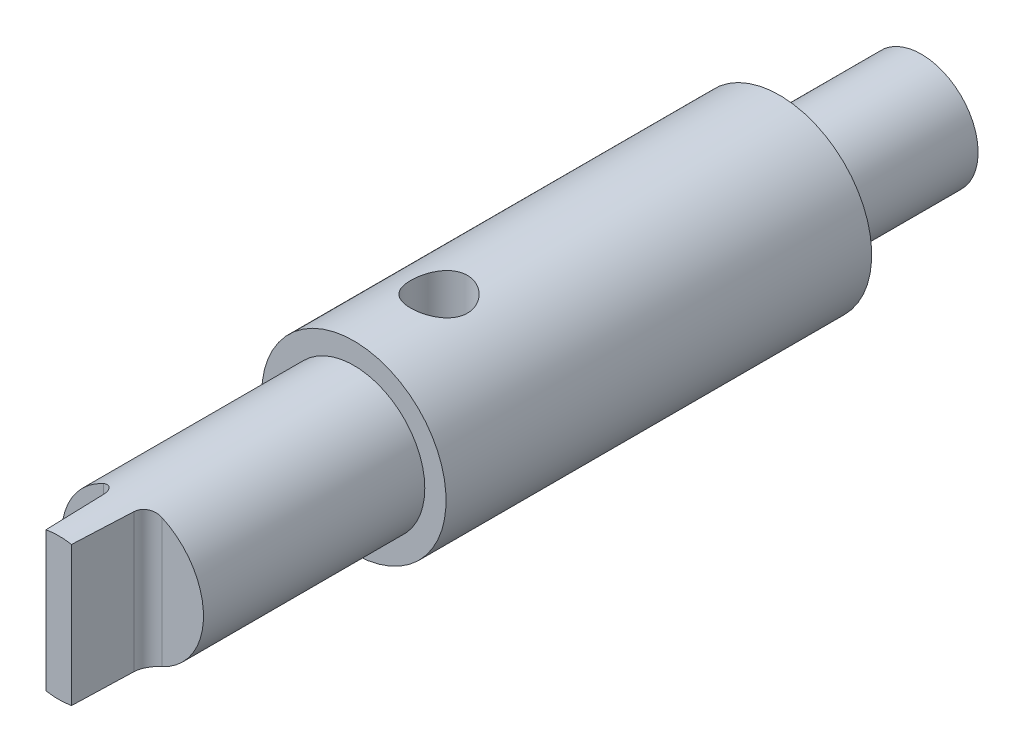
SolidWorks part; units mm, degrees
ref_plane "Спереди" through (0, 0, 0) normal (0, 0, 1) x (1, 0, 0)
ref_plane "Сверху" through (0, 0, 0) normal (0, 1, 0) x (1, 0, 0)
ref_plane "Справа" through (0, 0, 0) normal (1, 0, 0) x (0, 0, -1)
sketch "Эскиз1" plane through (0, 0, 0) normal (0, 0, 1) x (1, 0, 0)
  circle A0 centre (0, 0) radius 2.5
  dimension "D1" = 5
extrude "Бобышка-Вытянуть1" add sketch "Эскиз1" along normal blind 10.4
sketch "Эскиз2" plane through (0, 0, 0) normal (0, 0, -1) x (-1, 0, 0)
  circle A0 centre (0, 0) radius 3.25
  dimension "D1" = 6.5
extrude "Бобышка-Вытянуть2" add sketch "Эскиз2" along normal blind 15
sketch "Эскиз4" plane through (0, 0, 0) normal (0, 1, 0) x (1, 0, 0)
  line L0 (0, -10.4) -> (0, 0) construction
  line L1 (-2.5, -10.4) -> (2.5, -10.4) construction
  line L2 (-0.45, -10.4) -> (-0.55, -7.8)
  line L3 (-0.55, -7.8) -> (-2.5, -7.8)
  line L4 (-2.5, 0) -> (-2.5, -10.4) construction
  line L5 (-2.5, -7.8) -> (-2.5, -10.4)
  line L6 (-2.5, -10.4) -> (-0.45, -10.4)
  line L7 (0.45, -10.4) -> (0.55, -7.8)
  line L8 (0.55, -7.8) -> (2.5, -7.8)
  line L9 (2.5, -7.8) -> (2.5, -10.4)
  line L10 (2.5, -10.4) -> (0.45, -10.4)
  dimension "D1" = 0.45
  dimension "D2" = 0.55
  dimension "D3" = 2.6
extrude "Вырез-Вытянуть1" cut sketch "Эскиз4" against normal through all both and the other way through all
fillet "Скругление1" radius 0.5 2 edges at (0.55, 0, 7.8) (-0.55, 0, 7.8)
sketch "Эскиз5" plane through (0, 0, 0) normal (0, 1, 0) x (1, 0, 0)
  line L0 (-2.5, 0) -> (2.5, 0) construction
  circle A0 centre (0, 3) radius 1
  dimension "D2" = 2
  dimension "D1" = 3
extrude "Вырез-Вытянуть2" cut sketch "Эскиз5" against normal through all both and the other way through all
sketch "Эскиз6" plane through (0, 0, -15) normal (0, 0, -1) x (-1, 0, 0)
  circle A0 centre (0, 0) radius 2
  dimension "D1" = 4
extrude "Бобышка-Вытянуть3" add sketch "Эскиз6" along normal blind 5
